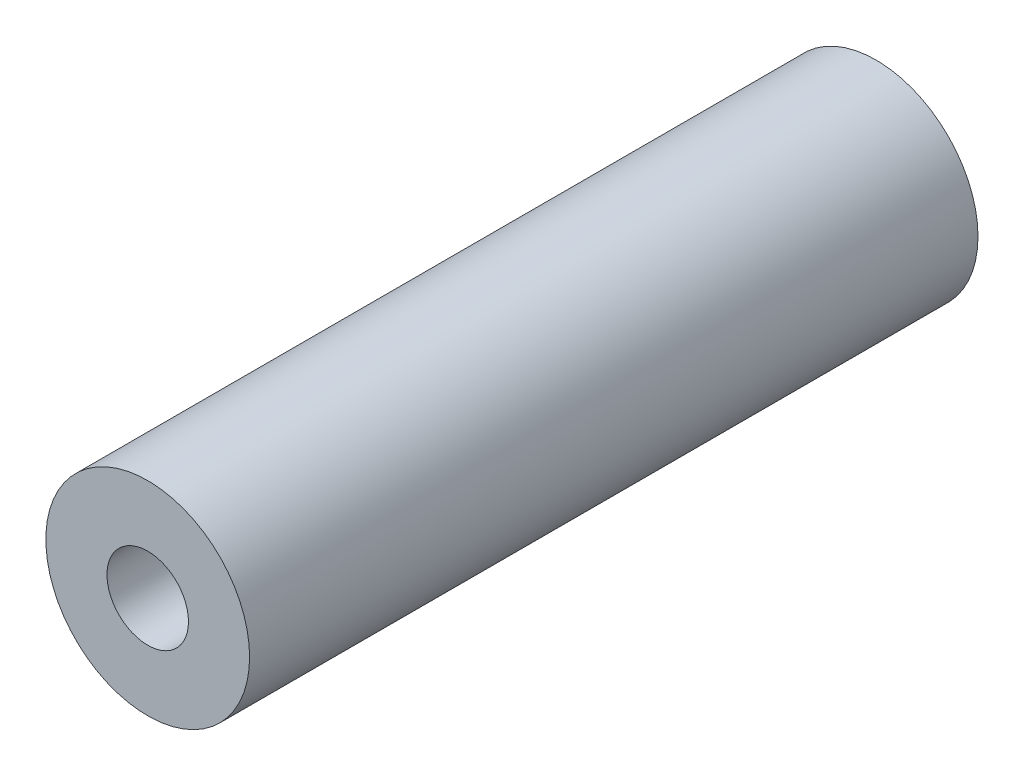
SolidWorks part; units mm, degrees
ref_plane "Front Plane" through (0, 0, 0) normal (0, 0, 1) x (1, 0, 0)
ref_plane "Top Plane" through (0, 0, 0) normal (0, 1, 0) x (1, 0, 0)
ref_plane "Right Plane" through (0, 0, 0) normal (1, 0, 0) x (0, 0, -1)
sketch "Standoff_OD8_ID3p2_profile" plane through (0, 0, 0) normal (0, 0, 1) x (1, 0, 0)
  circle A0 centre (0, 0) radius 4
  circle A1 centre (0, 0) radius 1.6
  dimension "D1" = 8
  dimension "D2" = 3.2
extrude "Standoff_OD8_ID3p2" add sketch "Standoff_OD8_ID3p2_profile" along normal blind 28.6
